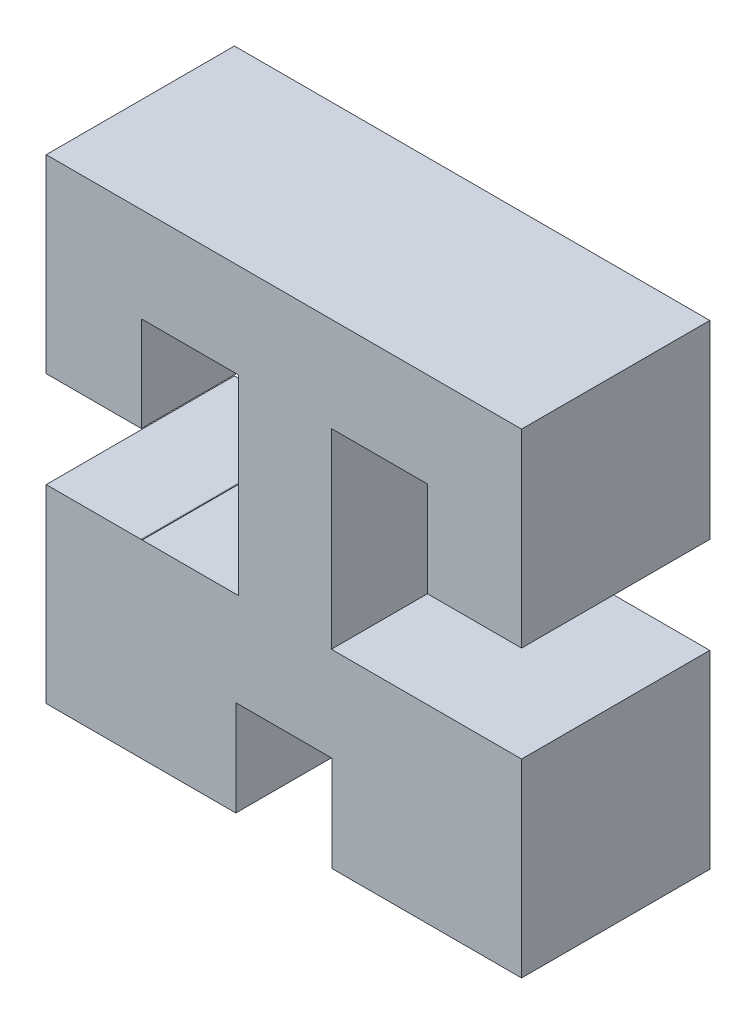
SolidWorks part; units mm, degrees
ref_plane "Front Plane" through (0, 0, 0) normal (0, 0, 1) x (1, 0, 0)
ref_plane "Top Plane" through (0, 0, 0) normal (0, 1, 0) x (1, 0, 0)
ref_plane "Right Plane" through (0, 0, 0) normal (1, 0, 0) x (0, 0, -1)
ref_plane "Plane1" through (0, 0, 0) normal (0, 0, -1) x (-1, 0, 0)
sketch "Sketch1" plane through (0, 0, 0) normal (0, 0, -1) x (-1, 0, 0)
  line L0 (30.05, 0) -> (30.05, 9.9735)
  line L1 (30.05, 9.9735) -> (25.049, 9.9735)
  line L2 (25.049, 9.9735) -> (25.049, 10)
  line L3 (25.049, 10) -> (25.001, 10)
  line L4 (25.001, 10) -> (25.001, 9.974)
  line L5 (25.001, 9.974) -> (19.949, 9.974)
  line L6 (19.949, 9.974) -> (19.949, 20.026)
  line L7 (19.949, 20.026) -> (25.001, 20.026)
  line L8 (25.001, 20.026) -> (25.001, 20)
  line L9 (25.001, 20) -> (25.05, 20)
  line L10 (25.05, 20) -> (25.05, 15.026)
  line L11 (25.05, 15.026) -> (30.05, 15.026)
  line L12 (30.05, 15.026) -> (30.05, 25)
  line L13 (30.05, 25) -> (5.05, 25)
  line L14 (5.05, 25) -> (5.05, 15.026)
  line L15 (5.05, 15.026) -> (9.999, 15.026)
  line L16 (9.999, 15.026) -> (9.999, 20.026)
  line L17 (9.999, 20.026) -> (15.0515, 20.026)
  line L18 (15.0515, 20.026) -> (15.0515, 9.9735)
  line L19 (15.0515, 9.9735) -> (10.051, 9.9735)
  line L20 (10.051, 9.9735) -> (5.05, 9.9735)
  line L21 (5.05, 9.9735) -> (5.05, 0)
  line L22 (5.05, 0) -> (15.024, 0)
  line L23 (15.024, 0) -> (15.024, 5.026)
  line L24 (15.024, 5.026) -> (20.0765, 5.026)
  line L25 (20.0765, 5.026) -> (20.0765, 0)
  line L26 (20.0765, 0) -> (30.05, 0)
  dimension "D1" = 25
extrude "Boss-Extrude1" add sketch "Sketch1" against normal blind 9.9
